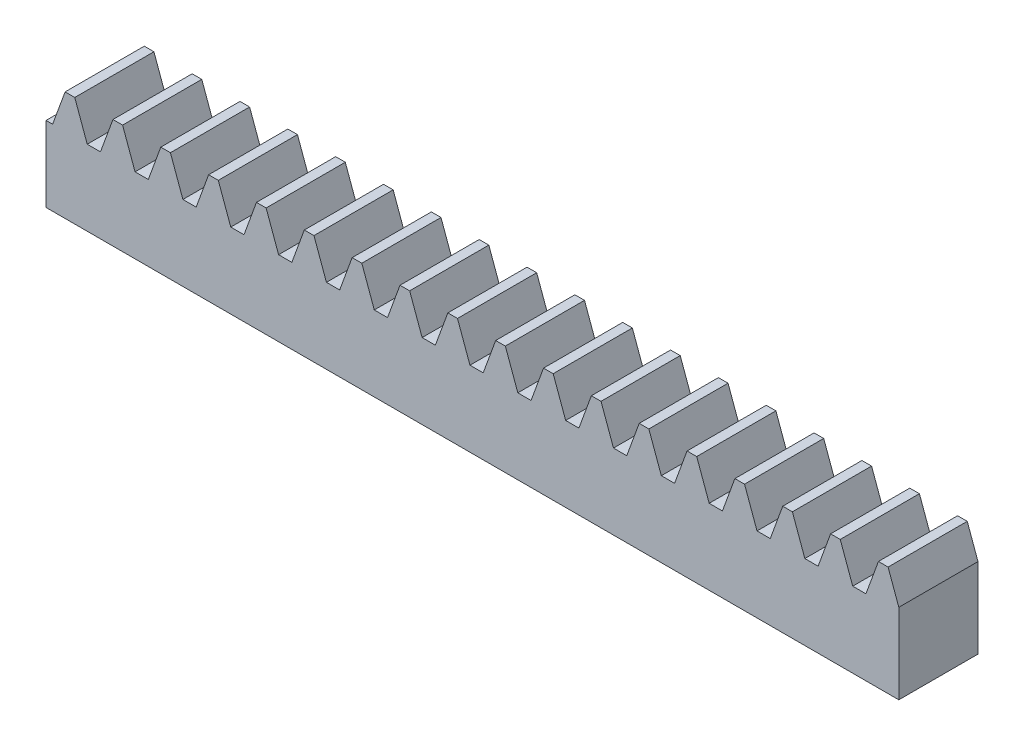
SolidWorks part; units mm, degrees
extrude "Blank" add sketch "BlankSke" against normal blind 15
sketch "BlankSke" plane through (0, 0, 0) normal (0, 0, 1) x (1, 0, 0)
  line L1 (0, 0) -> (140, 0)
  line L2 (0, 0) -> (0, 18)
  line L3 (0, 18) -> (140, 18)
  line L4 (140, 0) -> (140, 18)
  dimension "Length" = 140
  dimension "Blank_height" = 18
ref_plane "Plane1" through (0, 0, 0) normal (0, 0, 1) x (1, 0, 0)
ref_plane "Plane2" through (0, 0, 0) normal (0, 1, 0) x (1, 0, 0)
ref_plane "Plane3" through (0, 0, 0) normal (1, 0, 0) x (0, 0, -1)
other "Configuration Table"
sketch "HoldingSke" plane through (0, 0, 0) normal (0, 1, 0) x (1, 0, 0)
  line L0 (0, 0) -> (0.0557, 0.3961)
  line L1 (-15, 0) -> (100, 0) construction
  line L2 (0, 0) -> (-2.1039, 2.3779)
  line L3 (0, 0) -> (-11.863, 4.5341)
  line L4 (0, 0) -> (8.1655, 2.8116)
  line L5 (0, 0) -> (-23.7986, -8.8762)
  line L6 (0, 0) -> (-10.5278, -7.1032)
  line L9 (-71.009, 38.7566) -> (60.548, 86.6394)
  line L10 (-76.2, 4.8779) -> (-60.7, 4.8779)
  line L11 (0, 0) -> (-15, 0)
  line L12 (-76.2, 101.6) -> (-76.113, 101.6)
  line L13 (24.9733, 27.94) -> (52.9518, 28.4284)
  line L14 (24.9733, 27.94) -> (24.9743, 27.94)
  line L15 (24.9733, 27.94) -> (100.4006, 29.5858)
  circle A0 centre (0, 0) radius 19.05
  circle A1 centre (0, 0) radius 7.75
  circle A2 centre (0, 0) radius 12.7
  dimension "MPH" = 15.5
  dimension "Diameter" = 38.1
  dimension "Num_teeth" = 19
  dimension "Pitch" = 0.4
  dimension "Show_teeth" = 998
  dimension "Thickness" = 12.7
  dimension "Ap" = 20
  dimension "Pitch_height" = 15.5
  dimension "Width" = 15
  dimension "Backlash" = 0.087
  dimension "Addendum_fac" = 1
  dimension "Dedendum_fac" = 1.25
  dimension "Clearance_fac" = 0.25
  dimension "Dedendum_add" = 0.001
  dimension "Length" = 140
  dimension "Module" = 2.5
sketch "TooCutSkeIll" plane through (0, 0, 0) normal (0, 0, 1) x (1, 0, 0)
  line L0 (-3.1105, 17.9342) -> (-1.237, 12.7869)
  line L1 (-0.6488, 12.375) -> (0.6488, 12.375)
  line L2 (1.237, 12.7869) -> (3.1105, 17.9342)
  line L3 (140, 18) -> (0, 18) construction
  line L4 (0, 0) -> (0, 64.897) construction
  line L5 (-13.208, 15.5) -> (12.954, 15.5) construction
  line L6 (0, 0) -> (140, 0) construction
  line L7 (2.2245, 15.5) -> (2.2245, 48.7463) construction
  line L8 (-2.2245, 15.5) -> (-2.2245, 48.7463) construction
  line L9 (3.2044, 18) -> (3.2044, 18.0254)
  line L10 (-3.2044, 18) -> (-3.2044, 18.0254)
  line L11 (-3.2044, 18.0254) -> (3.2044, 18.0254)
  arc A0 (0.6488, 12.375) -> (1.237, 12.7869) centre (0.6488, 13.001) ccw
  arc A1 (-1.237, 12.7869) -> (-0.6488, 12.375) centre (-0.6488, 13.001) ccw
  arc A2 (3.2044, 18) -> (3.1105, 17.9342) centre (3.2044, 17.9) ccw
  arc A3 (-3.1105, 17.9342) -> (-3.2044, 18) centre (-3.2044, 17.9) ccw
  dimension "Pitch_height" = 15.5
  dimension "Addendum_plus" = 2.5254
  dimension "Pressure_angle" = 20
  dimension "Gap_width" = 4.449
  dimension "Dedendum" = 3.125
extrude "ToothCutIll" [suppressed] cut sketch "TooCutSkeIll" against normal through all
sketch "TooCutSkeSim" plane through (0, 0, 0) normal (0, 0, 1) x (1, 0, 0)
  line L0 (1.0871, 12.375) -> (-1.0871, 12.375)
  line L1 (3.1437, 18.0254) -> (1.0871, 12.375)
  line L2 (0, 17.4625) -> (0, 53.467) construction
  line L3 (3.1437, 18.0254) -> (-3.1437, 18.0254)
  line L6 (-3.1437, 18.0254) -> (-1.0871, 12.375)
  line L9 (-2.2245, 15.5) -> (2.2245, 15.5) construction
  line L10 (0, 0) -> (140, 0) construction
  line L11 (2.2245, 15.5) -> (2.2245, 53.467) construction
  line L12 (-2.2245, 15.5) -> (-2.2245, 53.467) construction
  dimension "Pitch_height" = 15.5
  dimension "Addendum_plus" = 2.5254
  dimension "Pressure_angle" = 20
  dimension "Gap_width" = 4.449
  dimension "Dedendum" = 3.125
extrude "ToothCutSim" cut sketch "TooCutSkeSim" against normal through all
pattern_linear "TeethCuts" count 18 spacing 7.854 along (1, 0, 0) of "ToothCutIll", "ToothCutSim"
sketch "Sketch1" plane through (0, 0, -15) normal (0, 0, 1) x (1, 0, 0)
  line L1 (-6.8194, 43.8859) -> (148.9081, 43.8859)
  line L2 (-6.8194, 43.8859) -> (-6.8194, -28.9972)
  line L3 (-6.8194, -28.9972) -> (148.9081, -28.9972)
  line L4 (148.9081, 43.8859) -> (148.9081, -28.9972)
extrude "Cut-Extrude2" cut sketch "Sketch1" along normal blind 2
equation "' \"Module@HoldingSke\" = 6.35"
equation "' \"Num_teeth@HoldingSke\" = 12"
equation "' \"Ap@HoldingSke\" =  20"
equation "' \"Ap@HoldingSke\" = 20"
equation "' \"Width@HoldingSke\" = 0.25 * 25.4"
equation "' \"Show_teeth@HoldingSke\" = 500"
equation "' \"Backlash@HoldingSke\" = 0.009 * 25.4"
equation "' \"Addendum_fac@HoldingSke\" = 1.0"
equation "' \"Dedendum_fac@HoldingSke\" = 1.25"
equation "' \"Dedendum_add@HoldingSke\" = 0.00005 * 25.4"
equation "' \"Clearance_fac@HoldingSke\" = 0.25"
equation "' \"Pitch_height@HoldingSke\" = 1 * 25.4"
equation "' \"Length@HoldingSke\" = 4.71 * 25.4"
equation "\"Pitch@HoldingSke\" = 1 / \"Module@HoldingSke\""
equation "\"MPH@HoldingSke\" = \"Dedendum_fac@HoldingSke\" / \"Pitch@HoldingSke\" + 2 * \"Dedendum_add@HoldingSke\" + 0.002 * 25.4"
equation "\"MPH@HoldingSke\" = ((sgn( \"MPH@HoldingSke\" - \"Pitch_height@HoldingSke\")+1)*( \"MPH@HoldingSke\" - \"Pitch_height@HoldingSke\"))/2 + \"Pitch_height@HoldingSke\""
equation "\"Blank_height@BlankSke\" = \"Pitch_height@HoldingSke\" + \"Addendum_fac@HoldingSke\"  / \"Pitch@HoldingSke\" "
equation "\"Length@BlankSke\" =  \"Length@HoldingSke\""
equation "\"Face_width@Blank\" = \"Width@HoldingSke\""
equation "\"Pressure_angle@TooCutSkeIll\" = \"Ap@HoldingSke\""
equation "\"Addendum_plus@TooCutSkeIll\" =  \"Addendum_fac@HoldingSke\"  / \"Pitch@HoldingSke\" + 0.001 *25.4"
equation "\"Dedendum@TooCutSkeIll\" = \"Dedendum_fac@HoldingSke\"  / \"Pitch@HoldingSke\""
equation "\"Pitch_height@TooCutSkeIll\" =  \"MPH@HoldingSke\""
equation "\"Gap_width@TooCutSkeIll\" = 3.14159265 / 2 / \"Pitch@HoldingSke\" + 6 * \"Backlash@HoldingSke\""
equation "\"Pressure_angle@TooCutSkeSim\" = \"Ap@HoldingSke\""
equation "\"Addendum_plus@TooCutSkeSim\" =  \"Addendum_fac@HoldingSke\"  / \"Pitch@HoldingSke\" + 0.001 * 25.4"
equation "\"Dedendum@TooCutSkeSim\" = \"Dedendum_fac@HoldingSke\"  / \"Pitch@HoldingSke\""
equation "\"Pitch_height@TooCutSkeSim\" =  \"MPH@HoldingSke\""
equation "\"Gap_width@TooCutSkeSim\" = 3.14159265 / 2 / \"Pitch@HoldingSke\" + 6 * \"Backlash@HoldingSke\""
equation "\"Root_fillet@TooCutSkeIll\" = \"Clearance_fac@HoldingSke\" / \"Pitch@HoldingSke\" + \"Dedendum_add@HoldingSke\""
equation "\"Break_rad@TooCutSkeIll\" = 0.02 / \"Pitch@HoldingSke\" * 2"
equation "\"Linear_pitch@TeethCuts\" = 3.14159265 / \"Pitch@HoldingSke\""
equation "\"Num_teeth@HoldingSke\" = int( ( \"Length@HoldingSke\" + 0 ) / (3.14159265 / \"Pitch@HoldingSke\")) + 0.9999  + 1"
equation " \"Num_teeth@TeethCuts\" = int( \"Show_teeth@HoldingSke\" ) + 1"
equation " \"Num_teeth@TeethCuts\" = ((sgn( \"Num_teeth@TeethCuts\" - \"Num_teeth@HoldingSke\" )-1)*( \"Num_teeth@TeethCuts\" - \"Num_teeth@HoldingSke\" ))/-2+ \"Num_teeth@HoldingSke\""
equation " \"Num_teeth@TeethCuts\" = ((sgn( \"Num_teeth@TeethCuts\" - 2.0)+1)*( \"Num_teeth@TeethCuts\" - 2.0))/2 +2.0"
